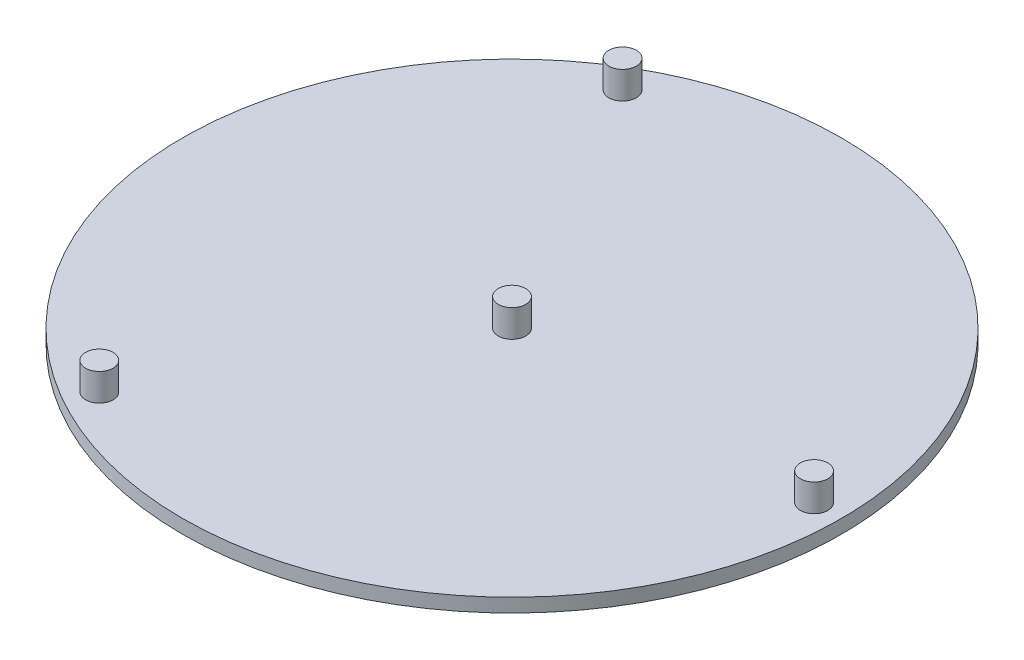
SolidWorks part; units mm, degrees
ref_plane "Front Plane" through (0, 0, 0) normal (0, 0, 1) x (1, 0, 0)
ref_plane "Top Plane" through (0, 0, 0) normal (0, 1, 0) x (1, 0, 0)
ref_plane "Right Plane" through (0, 0, 0) normal (1, 0, 0) x (0, 0, -1)
sketch "Sketch1" plane through (0, 0, 0) normal (0, 1, 0) x (1, 0, 0)
  circle A0 centre (0, 0) radius 76.2
  dimension "D1" = 152.4
extrude "Boss-Extrude1" add sketch "Sketch1" along normal blind 3.175
sketch "Sketch3" plane through (0, 3.175, 0) normal (0, 1, 0) x (1, 0, 0)
  line L0 (0, 0) -> (76.2, 0) construction
  circle A0 centre (0, 0) radius 3.175
  circle A1 centre (0, 0) radius 76.2 construction
  circle A2 centre (69.85, 0) radius 3.175
  dimension "D1" = 6.35
  dimension "D2" = 6.35
  dimension "D3" = 6.35
extrude "Boss-Extrude2" add sketch "Sketch3" along normal blind 6.35
pattern_circular "CirPattern1" count 3 over 360 about axis through (0, 0, 0) along (0, 1, 0) of "Boss-Extrude2"
